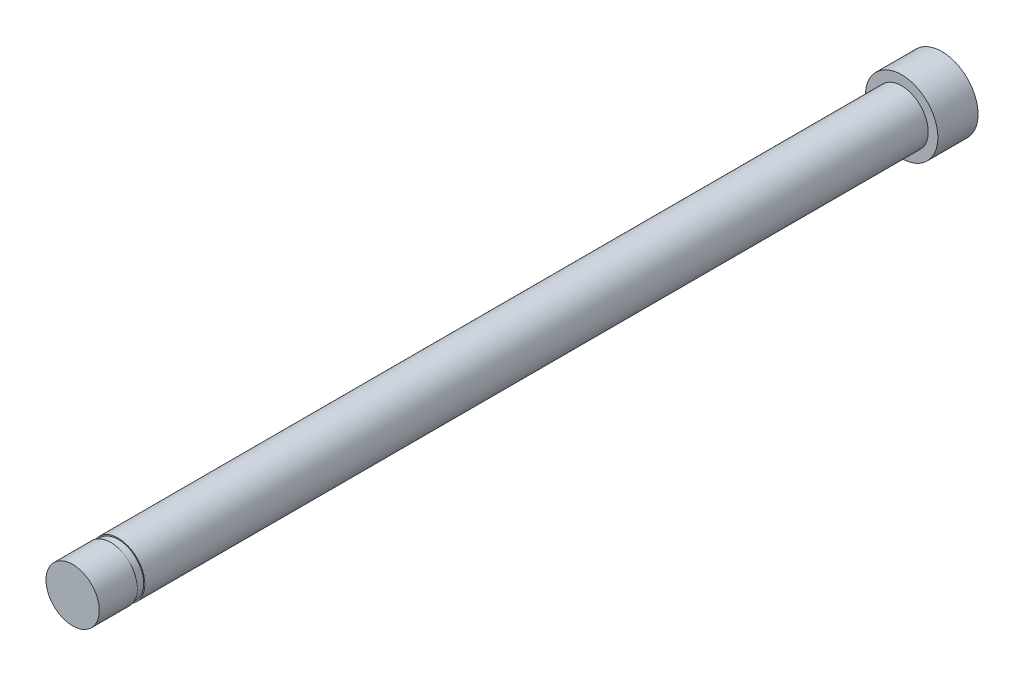
SolidWorks part; units mm, degrees
ref_plane "Front Plane" through (0, 0, 0) normal (0, 0, 1) x (1, 0, 0)
ref_plane "Top Plane" through (0, 0, 0) normal (0, 1, 0) x (1, 0, 0)
ref_plane "Right Plane" through (0, 0, 0) normal (1, 0, 0) x (0, 0, -1)
sketch "Sketch1" plane through (0, 0, 0) normal (0, 0, 1) x (1, 0, 0)
  circle A0 centre (0, 0) radius 2.5
  dimension "D1" = 5
extrude "Boss-Extrude1" add sketch "Sketch1" along normal mid plane 81.534
ref_axis "Axis1" through (0, 0, 40.767) along (0, 0, -1)
sketch "Sketch2" plane through (0, 0, 0) normal (1, 0, 0) x (0, 0, -1)
  line L0 (40.767, 2.5) -> (-40.767, 2.5) construction
  line L1 (-37.198, 2.5) -> (-36.498, 2.5)
  line L2 (-37.198, 2.5) -> (-37.198, 2.4)
  line L3 (-37.198, 2.4) -> (-36.498, 2.4)
  line L4 (-36.498, 2.5) -> (-36.498, 2.4)
  line L5 (-36.498, 67.9355) -> (-36.498, -18.3518) construction
  dimension "D1" = 0.1
  dimension "D2" = 0.7
revolve "Cut-Revolve1" cut sketch "Sketch2" angle 360 about axis through (0, 0, 40.767) along (0, 0, -1)
sketch "Sketch4" plane through (0, 0, -40.767) normal (0, 0, -1) x (-1, 0, 0)
  circle A0 centre (0, 0) radius 3.4022
extrude "Boss-Extrude2" add sketch "Sketch4" against normal up to surface (3.7722 mm away)
